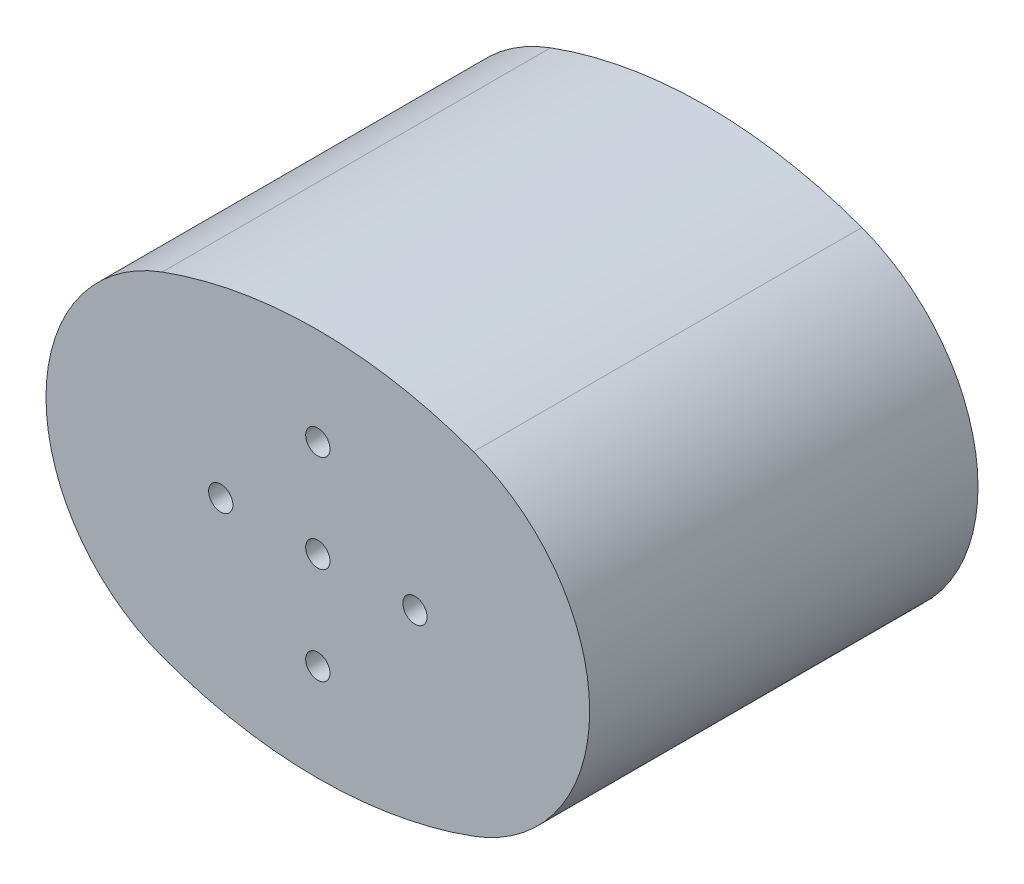
SolidWorks part; units mm, degrees
ref_plane "Front Plane" through (0, 0, 0) normal (0, 0, 1) x (1, 0, 0)
ref_plane "Top Plane" through (0, 0, 0) normal (0, 1, 0) x (1, 0, 0)
ref_plane "Right Plane" through (0, 0, 0) normal (1, 0, 0) x (0, 0, -1)
sketch "Sketch1" plane through (0, 0, 0) normal (0, 0, 1) x (1, 0, 0)
  line L0 (0, 0) -> (24856.2268, 0) construction
  line L1 (0, -3.4133) -> (0, 24852.8136) construction
  arc A0 (-16.0304, 17.1488) -> (-16.0304, -17.1488) centre (-9.7308, 0) ccw
  arc A2 (16.0304, -17.1488) -> (16.0304, 17.1488) centre (9.7308, 0) ccw
  arc A3 (16.0304, 17.1488) -> (-16.0304, 17.1488) centre (0, -26.489) ccw
  arc A4 (-16.0304, -17.1488) -> (16.0304, -17.1488) centre (0, 26.489) ccw
  point P6 (0, 20)
  point P13 (0, -20)
  point P14 (-28, 0)
  point P15 (28, 0)
  dimension "D4" = 56
  dimension "D5" = 40
extrude "Boss-Extrude1" add sketch "Sketch1" along normal blind 40
sketch "Sketch2" plane through (0, 0, 40) normal (0, 0, 1) x (1, 0, 0)
  line L0 (0, 0) -> (50000, 0) construction
  line L1 (0, 0) -> (0, 50000) construction
  circle A0 centre (0, 10) radius 1.25
  circle A4 centre (10, 0) radius 1.25
  circle A5 centre (0, -10) radius 1.25
  circle A6 centre (-10, 0) radius 1.25
  circle A7 centre (0, 0) radius 1.25
  point P16 (0, 0)
  dimension "D1" = 2.5
  dimension "D3" = 4
  dimension "D2" = 10
extrude "Cut-Extrude1" cut sketch "Sketch2" against normal through all
